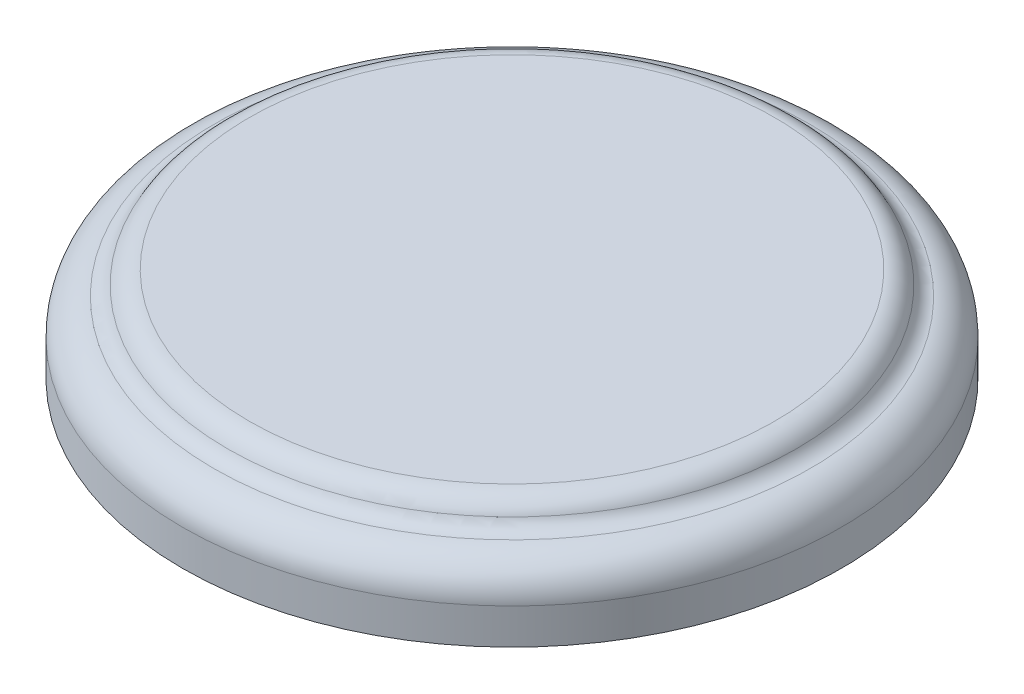
SolidWorks part; units mm, degrees
ref_plane "Front Plane" through (0, 0, 0) normal (0, 0, 1) x (1, 0, 0)
ref_plane "Top Plane" through (0, 0, 0) normal (0, 1, 0) x (1, 0, 0)
ref_plane "Right Plane" through (0, 0, 0) normal (1, 0, 0) x (0, 0, -1)
sketch "Sketch1" plane through (0, 0, 0) normal (1, 0, 0) x (0, 0, -1)
  line L0 (0, 0) -> (-177.8, 0)
  line L1 (-177.8, 0) -> (-177.8, 38.1)
  line L2 (-177.8, 38.1) -> (-152.4, 38.1)
  line L3 (-152.4, 38.1) -> (-152.4, 50.8)
  line L4 (-152.4, 50.8) -> (0, 50.8)
  line L5 (0, 50.8) -> (0, 0)
  dimension "D1" = 50.8
  dimension "D2" = 12.7
  dimension "D3" = 25.4
  dimension "D4" = 177.8
revolve "Revolve1" add sketch "Sketch1" angle 360 about L5
fillet "Fillet1" radius 9.525 1 edges at (0, 38.1, 152.4)
fillet "Fillet2" radius 19.05 1 edges at (0, 38.1, 177.8)
fillet "Fillet3" radius 12.7 1 edges at (0, 50.8, 152.4)
shell "Shell1" thickness 3.175
